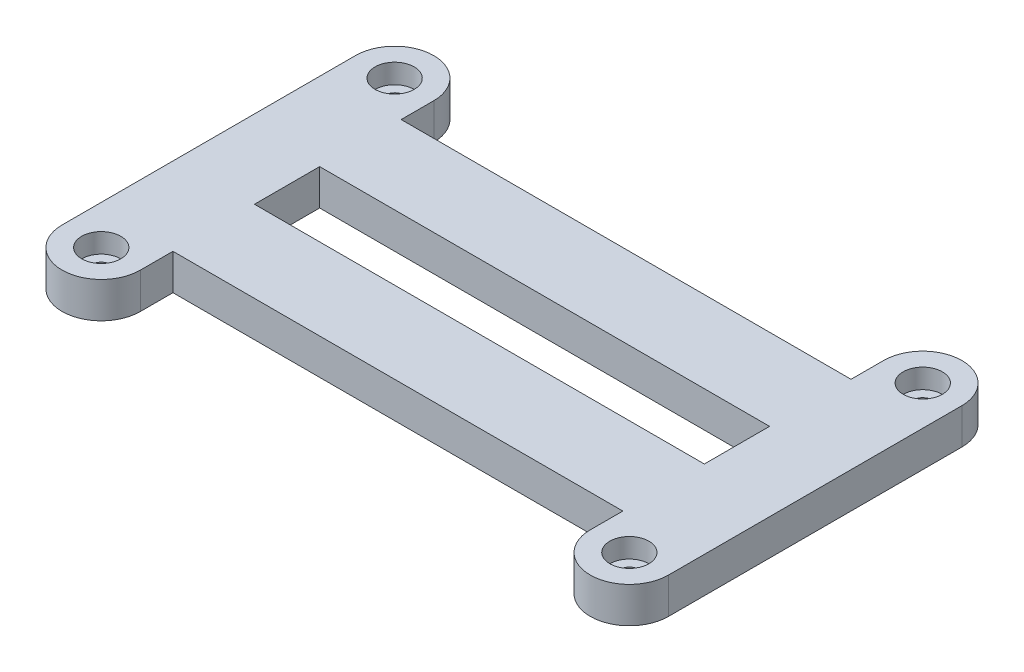
SolidWorks part; units mm, degrees
ref_plane "前视基准面" through (0, 0, 0) normal (0, 0, 1) x (1, 0, 0)
ref_plane "上视基准面" through (0, 0, 0) normal (0, 1, 0) x (1, 0, 0)
ref_plane "右视基准面" through (0, 0, 0) normal (1, 0, 0) x (0, 0, -1)
sketch "草图1" plane through (0, 0, 0) normal (0, 1, 0) x (1, 0, 0)
  line L0 (46.5, 22.5) -> (46.5, -22.5)
  line L1 (34.5, 22.5) -> (34.5, 17.5)
  line L2 (-34.5, 17.5) -> (34.5, 17.5)
  line L3 (-34.5, 5) -> (34.5, 5)
  line L4 (34.5, 5) -> (34.5, -5)
  line L5 (0, 45.851) -> (0, 5) construction
  line L6 (0, 0) -> (79.8383, 0) construction
  line L7 (-34.5, -5) -> (34.5, -5)
  line L8 (-34.5, -17.5) -> (34.5, -17.5)
  line L9 (34.5, -22.5) -> (34.5, -17.5)
  line L10 (-34.5, -22.5) -> (-34.5, -17.5)
  line L11 (-34.5, 5) -> (-34.5, -5)
  line L12 (-34.5, 22.5) -> (-34.5, 17.5)
  line L13 (-46.5, 22.5) -> (-46.5, -22.5)
  circle A0 centre (40.5, 22.5) radius 1.5
  arc A1 (46.5, 22.5) -> (34.5, 22.5) centre (40.5, 22.5) ccw
  arc A8 (46.5, -22.5) -> (34.5, -22.5) centre (40.5, -22.5) cw
  circle A9 centre (40.5, -22.5) radius 1.5
  circle A10 centre (-40.5, -22.5) radius 1.5
  arc A11 (-46.5, -22.5) -> (-34.5, -22.5) centre (-40.5, -22.5) ccw
  arc A12 (-46.5, 22.5) -> (-34.5, 22.5) centre (-40.5, 22.5) cw
  circle A13 centre (-40.5, 22.5) radius 1.5
  point P11 (34.5, 0)
  point P12 (46.5, 0)
  point P16 (-46.5, 0)
  point P30 (0, -17.5)
  point P32 (0, -5)
  point P34 (0, 17.5)
  point P35 (-34.5, 0)
  dimension "D1" = 3
  dimension "D4" = 12
extrude "凸台-拉伸3" add sketch "草图1" along normal blind 5.5
sketch "草图2" plane through (0, 5.5, 0) normal (0, 1, 0) x (1, 0, 0)
  line L0 (0, 0) -> (0, 44.3437) construction
  line L1 (0, 0) -> (87.4525, 0) construction
  circle A0 centre (40.5, 22.5) radius 3
  circle A1 centre (40.5, -22.5) radius 3
  circle A2 centre (-40.5, -22.5) radius 3
  circle A3 centre (-40.5, 22.5) radius 3
extrude "切除-拉伸1" cut sketch "草图2" against normal blind 3
